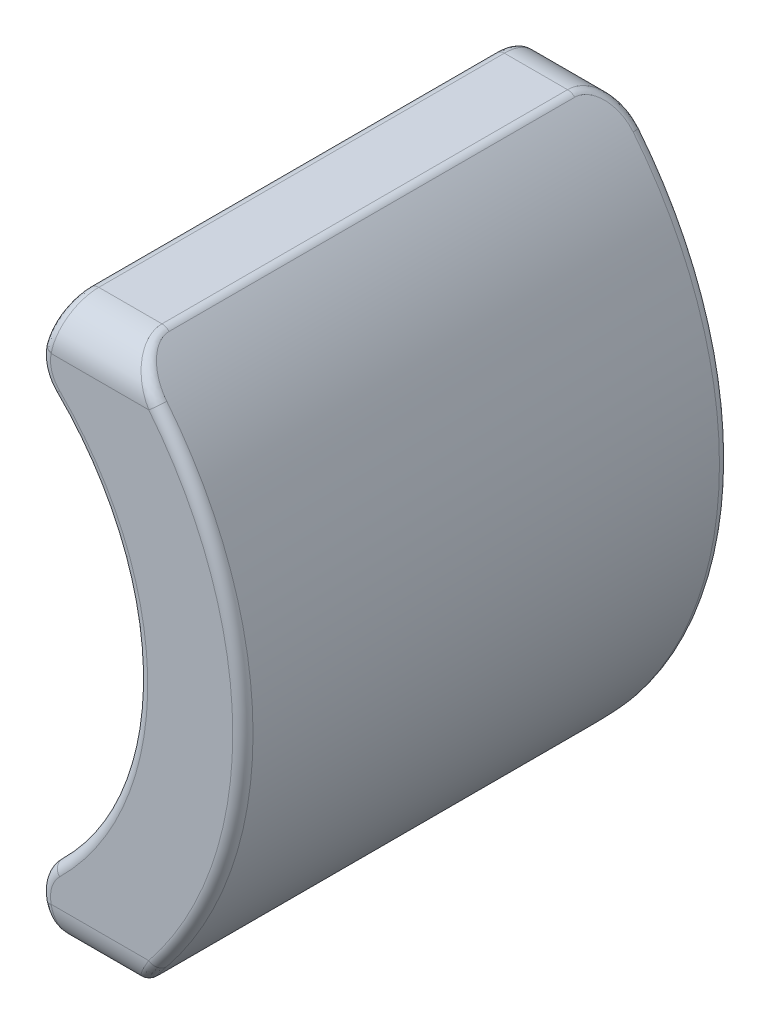
SolidWorks part; units mm, degrees
ref_plane "Front Plane" through (0, 0, 0) normal (0, 0, 1) x (1, 0, 0)
ref_plane "Top Plane" through (0, 0, 0) normal (0, 1, 0) x (1, 0, 0)
ref_plane "Right Plane" through (0, 0, 0) normal (1, 0, 0) x (0, 0, -1)
sketch "Sketch1" plane through (0, 0, 0) normal (0, 0, 1) x (1, 0, 0)
  line L0 (0, 0) -> (9.63, 0) construction
  line L1 (6.7381, -6.88) -> (4.8781, -6.88)
  line L2 (4.8781, -6.88) -> (4.5318, -5.38)
  line L3 (6.7381, 6.88) -> (4.8781, 6.88)
  line L4 (4.8781, 6.88) -> (4.5318, 5.38)
  arc A0 (6.7381, 6.88) -> (6.7381, -6.88) centre (0, 0) cw
  arc A1 (4.5318, 5.38) -> (4.5318, -5.38) centre (0, 0) cw
  dimension "D1" = 9.63
  dimension "D2" = 6.88
  dimension "D3" = 103
  dimension "D4" = 1.86
  dimension "D5" = 1.5
extrude "Boss-Extrude1" add sketch "Sketch1" along normal blind 12
fillet "Fillet1" radius 1 2 edges at (4.5318, -5.38, 6) (4.5318, 5.38, 6)
fillet "Fillet2" radius 1 4 edges at (5.8081, -6.88, 12) (5.8081, -6.88, 0) (5.8081, 6.88, 12) (5.8081, 6.88, 0)
fillet "Fillet3" radius 0.25 24 edges at (6.9882, -6.6258, 11.6661) (6.7381, -6.88, 6) (6.8685, -6.7498, 0.5066) (9.63, 0, 0) (6.9882, 6.6258, 0.3339) (6.7381, 6.88, 6) (6.8685, 6.7498, 11.4934) (4.8161, 6.6112, 11.6822) (4.8781, 6.88, 6) (4.8161, 6.6112, 0.3178) (4.6879, 5.4113, 0) (7.0343, 0, 0) (4.6879, -5.4113, 0) (4.8161, -6.6112, 0.3178) (4.8781, -6.88, 6) (4.8161, -6.6112, 11.6822) (7.0343, 0, 12) (4.6879, 5.4113, 12) (9.63, 0, 12) (4.6879, -5.4113, 12)
